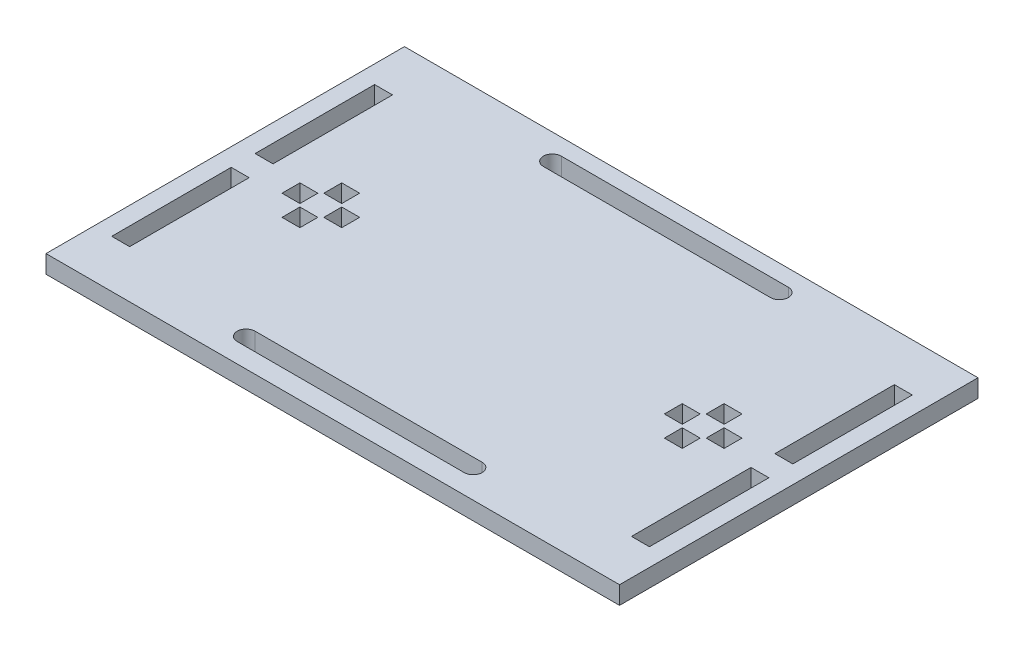
SolidWorks part; units mm, degrees
ref_plane "前视基准面" through (0, 0, 0) normal (0, 0, 1) x (1, 0, 0)
ref_plane "上视基准面" through (0, 0, 0) normal (0, 1, 0) x (1, 0, 0)
ref_plane "右视基准面" through (0, 0, 0) normal (1, 0, 0) x (0, 0, -1)
other "Configuration Table"
sketch "草图1" plane through (0, 0, 0) normal (0, 1, 0) x (1, 0, 0)
  line L0 (53.75, 0) -> (53.75, -60)
  line L9 (5.75, -0.25) -> (101.75, -0.25)
  line L22 (8.75, -32.25) -> (11.75, -32.25)
  line L23 (8.75, -8.25) -> (11.75, -8.25)
  line L24 (8.75, -8.25) -> (8.75, -28.25)
  line L25 (8.75, -28.25) -> (11.75, -28.25)
  line L26 (11.75, -8.25) -> (11.75, -28.25)
  line L27 (11.75, -52.25) -> (11.75, -32.25)
  line L28 (8.75, -52.25) -> (11.75, -52.25)
  line L29 (8.75, -52.25) -> (8.75, -32.25)
  line L30 (98.75, -28.25) -> (95.75, -28.25)
  line L31 (95.75, -8.25) -> (95.75, -28.25)
  line L32 (98.75, -8.25) -> (95.75, -8.25)
  line L33 (98.75, -8.25) -> (98.75, -28.25)
  line L34 (98.75, -52.25) -> (98.75, -32.25)
  line L35 (98.75, -52.25) -> (95.75, -52.25)
  line L36 (95.75, -52.25) -> (95.75, -32.25)
  line L37 (98.75, -32.25) -> (95.75, -32.25)
  line L38 (5.75, -0.25) -> (5.75, -60.25)
  line L39 (101.75, -0.25) -> (101.75, -60.25)
  line L40 (101.75, -60.25) -> (5.75, -60.25)
  line L49 (34.5, -54) -> (72.5, -54)
  line L50 (34.75, -6) -> (72.75, -6)
  line L51 (72.75, -3) -> (34.75, -3)
  line L52 (34.5, -57) -> (72.5, -57)
  line L61 (16.75, -28.75) -> (19.75, -28.75)
  line L62 (16.75, -25.25) -> (26.75, -25.25)
  line L63 (16.75, -25.25) -> (16.75, -35.25)
  line L64 (16.75, -35.25) -> (26.75, -35.25)
  line L65 (26.75, -25.25) -> (26.75, -35.25)
  line L66 (16.75, -25.25) -> (26.75, -35.25) construction
  line L67 (16.75, -35.25) -> (26.75, -25.25) construction
  line L68 (20.25, -35.25) -> (23.25, -35.25)
  line L69 (20.25, -35.25) -> (20.25, -32.25)
  line L70 (20.25, -32.25) -> (23.25, -32.25)
  line L71 (23.25, -35.25) -> (23.25, -32.25)
  line L72 (16.75, -28.75) -> (16.75, -31.75)
  line L73 (16.75, -31.75) -> (19.75, -31.75)
  line L74 (19.75, -28.75) -> (19.75, -31.75)
  line L75 (23.25, -25.25) -> (23.25, -28.25)
  line L76 (23.25, -25.25) -> (20.25, -25.25)
  line L77 (20.25, -25.25) -> (20.25, -28.25)
  line L78 (23.25, -28.25) -> (20.25, -28.25)
  line L79 (26.75, -31.75) -> (23.75, -31.75)
  line L80 (26.75, -31.75) -> (26.75, -28.75)
  line L81 (26.75, -28.75) -> (23.75, -28.75)
  line L82 (23.75, -31.75) -> (23.75, -28.75)
  line L83 (90.75, -28.75) -> (90.75, -31.75)
  line L84 (90.75, -31.75) -> (87.75, -31.75)
  line L85 (87.75, -28.75) -> (87.75, -31.75)
  line L86 (90.75, -28.75) -> (87.75, -28.75)
  line L87 (80.75, -31.75) -> (80.75, -28.75)
  line L88 (80.75, -28.75) -> (83.75, -28.75)
  line L89 (83.75, -31.75) -> (83.75, -28.75)
  line L90 (80.75, -31.75) -> (83.75, -31.75)
  line L91 (84.25, -25.25) -> (87.25, -25.25)
  line L92 (87.25, -25.25) -> (87.25, -28.25)
  line L93 (84.25, -28.25) -> (87.25, -28.25)
  line L94 (84.25, -25.25) -> (84.25, -28.25)
  line L95 (87.25, -32.25) -> (84.25, -32.25)
  line L96 (84.25, -35.25) -> (84.25, -32.25)
  line L97 (87.25, -35.25) -> (84.25, -35.25)
  line L98 (87.25, -35.25) -> (87.25, -32.25)
  circle A0 centre (72.75, -4.5) radius 1.5
  circle A1 centre (34.75, -4.5) radius 1.5
  circle A2 centre (72.5, -55.5) radius 1.5
  circle A3 centre (34.5, -55.5) radius 1.5
  circle A4 centre (21.75, -30.25) radius 5
  point P0 (21.75, -30.25)
  dimension "D10" = 3
  dimension "D11" = 19
  dimension "D12" = 10
  dimension "D13" = 3
  dimension "D14" = 30
  dimension "D15" = 3
  dimension "D2" = 10
  dimension "D3" = 3
  dimension "D4" = 3
  dimension "D5" = 96
  dimension "D6" = 3.5
  dimension "D7" = 3
  dimension "D8" = 20
  dimension "D9" = 4
  dimension "D16" = 3
extrude "凸台-拉伸2" add sketch "草图1" along normal blind 3
